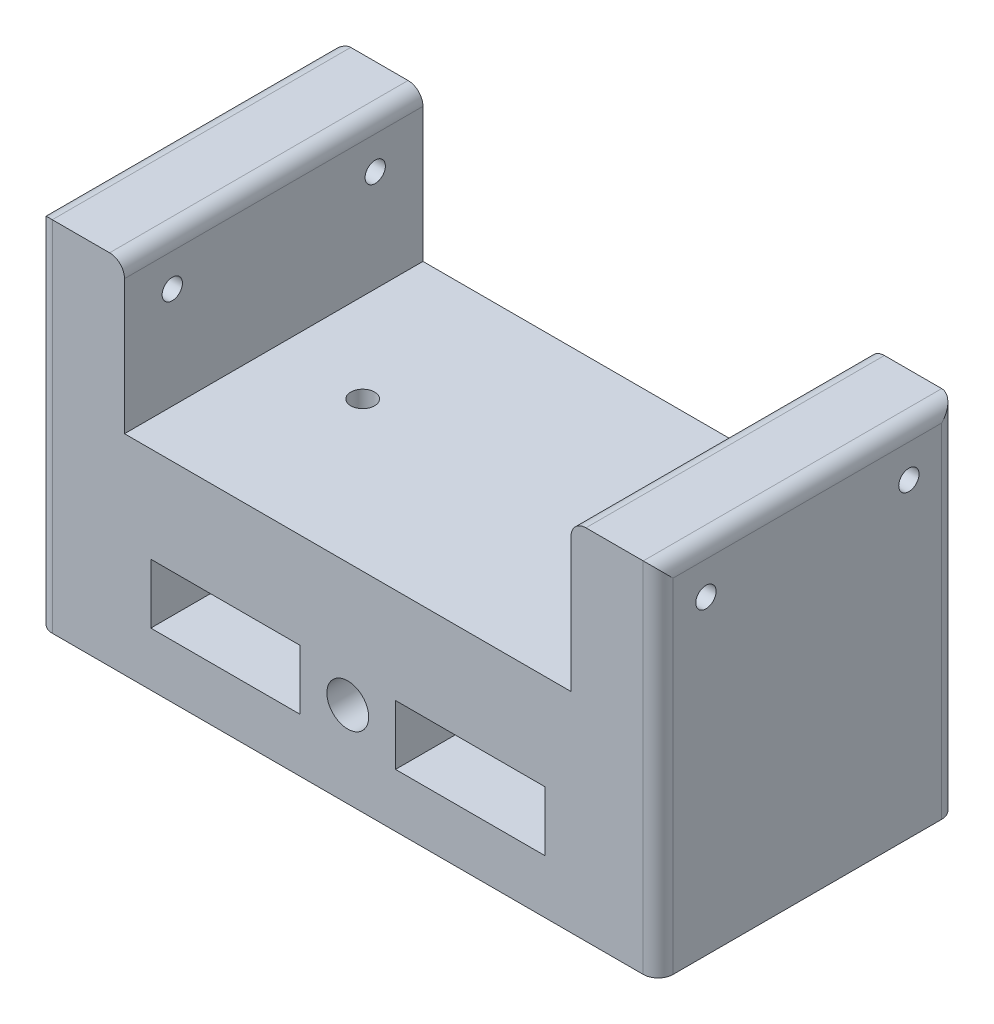
SolidWorks part; units mm, degrees
ref_plane "Front Plane" through (0, 0, 0) normal (0, 0, 1) x (1, 0, 0)
ref_plane "Top Plane" through (0, 0, 0) normal (0, 1, 0) x (1, 0, 0)
ref_plane "Right Plane" through (0, 0, 0) normal (1, 0, 0) x (0, 0, -1)
sketch "Sketch1" plane through (0, 0, 0) normal (0, 1, 0) x (1, 0, 0)
  line L0 (-63.2444, 0) -> (60.1177, 0) construction
  line L1 (-52, 25) -> (-52, -25)
  line L2 (-52, -25) -> (52, -25)
  line L3 (52, -25) -> (52, 25)
  line L4 (-52, 25) -> (52, 25)
  line L5 (0, -25) -> (0, 25) construction
  point P8 (52, 0)
  point P9 (-52, 0)
  dimension "D1" = 52
  dimension "D2" = 52
  dimension "D3" = 25
extrude "Boss-Extrude1" add sketch "Sketch1" along normal blind 10
sketch "Sketch2" plane through (0, 0, 0) normal (0, -1, 0) x (1, 0, 0)
  line L0 (0, 25) -> (0, -25) construction
  line L1 (-52, 25) -> (52, 25) construction
  line L2 (52, -25) -> (-52, -25) construction
  line L3 (-52, 0) -> (52, 0) construction
  line L4 (-52, -25) -> (-52, 25) construction
  line L5 (52, 25) -> (52, -25) construction
  line L6 (-45.5, 13.5) -> (-45.5, 0)
  line L7 (-45.5, 0) -> (-45.5, -13.5)
  line L8 (-45.5, -13.5) -> (0, -13.5)
  line L9 (0, -13.5) -> (45.5, -13.5)
  line L10 (45.5, -13.5) -> (45.5, 0)
  line L11 (45.5, 0) -> (45.5, 13.5)
  line L12 (45.5, 13.5) -> (0, 13.5)
  line L13 (0, 13.5) -> (-45.5, 13.5)
  line L14 (-52, 25) -> (52, 25)
  line L15 (52, 25) -> (52, -25)
  line L16 (52, -25) -> (-52, -25)
  line L17 (-52, -25) -> (-52, 25)
  dimension "D1" = 13.5
  dimension "D2" = 45.5
extrude "Boss-Extrude2" add sketch "Sketch2" along normal blind 25
sketch "Sketch3" plane through (0, 10, 0) normal (0, 1, 0) x (1, 0, 0)
  line L0 (0, 25) -> (0, -25) construction
  line L1 (52, 25) -> (-52, 25) construction
  line L2 (-52, -25) -> (52, -25) construction
  line L3 (-52, 25) -> (-37.4, 25)
  line L4 (-37.4, 25) -> (-37.4, -25)
  line L5 (-37.4, -25) -> (-52, -25)
  line L6 (-52, -25) -> (-52, 25)
  line L7 (37.4, 25) -> (52, 25)
  line L8 (52, 25) -> (52, -25)
  line L9 (52, -25) -> (37.4, -25)
  line L10 (37.4, -25) -> (37.4, 25)
  dimension "D1" = 74.8
extrude "Boss-Extrude3" add sketch "Sketch3" along normal blind 25
sketch "Sketch4" plane through (52, 0, 0) normal (1, 0, 0) x (0, 0, -1)
  line L0 (0, 35) -> (0, -25) construction
  line L1 (-25, 35) -> (25, 35) construction
  line L2 (25, -25) -> (-25, -25) construction
  line L3 (25, 35) -> (25, -25) construction
  circle A1 centre (17, 27) radius 1.7
  circle A2 centre (-17, 27) radius 1.7
  dimension "D1" = 8
  dimension "D2" = 3.4
  dimension "D3" = 8
extrude "Cut-Extrude1" cut sketch "Sketch4" against normal through all and the other way through all
sketch "Sketch5" plane through (0, 10, 0) normal (0, 1, 0) x (1, 0, 0)
  line L0 (-37.4, 0) -> (37.4, 0) construction
  line L1 (-37.4, -25) -> (-37.4, 25) construction
  line L2 (37.4, 25) -> (37.4, -25) construction
  line L3 (0, 25) -> (0, -25) construction
  line L4 (37.4, 25) -> (-37.4, 25) construction
  line L5 (-37.4, -25) -> (37.4, -25) construction
  circle A0 centre (-22.5, 0) radius 2
  circle A1 centre (22.5, 0) radius 2
  dimension "D1" = 4
  dimension "D2" = 4
  dimension "D3" = 45
extrude "Cut-Extrude2" cut sketch "Sketch5" against normal through all and the other way through all
sketch "Sketch8" plane through (0, 0, 25) normal (0, 0, 1) x (1, 0, 0)
  line L0 (0, 0) -> (0, -25) construction
  line L1 (52, -25) -> (-52, -25) construction
  line L3 (45.5, 0) -> (-45.5, 0) construction
  circle A0 centre (0, -10.65) radius 3.5
  dimension "D1" = 7
  dimension "D2" = 10.65
extrude "Cut-Extrude4" cut sketch "Sketch8" against normal up to next and the other way through all
fillet "Fillet1" radius 2.5 8 edges at (-52, 5, -25) (52, 5, -25) (52, 5, 25) (-52, 5, 25) (-52, 35, 0) (52, 35, 0) (37.4, 35, 0) (-37.4, 35, 0)
sketch "Sketch9" plane through (0, 0, -25) normal (0, 0, -1) x (-1, 0, 0)
  line L0 (0, 10) -> (0, -25) construction
  line L1 (-37.4, 10) -> (37.4, 10) construction
  line L2 (49.5, -25) -> (-49.5, -25) construction
  line L5 (-33, -6) -> (-33, -16)
  line L8 (-33, -6) -> (0, -6)
  line L11 (33, -6) -> (33, -16)
  line L13 (0, -6) -> (33, -6)
  line L14 (-33, -16) -> (0, -16)
  line L15 (0, -16) -> (33, -16)
  dimension "D1" = 33
  dimension "D2" = 9
  dimension "D4" = 10
extrude "Cut-Extrude6" cut sketch "Sketch9" against normal up to next and the other way through all
sketch "Sketch10" plane through (0, 0, 25) normal (0, 0, 1) x (1, 0, 0)
  line L0 (0, 0) -> (0, -25) construction
  line L1 (45.5, 0) -> (-45.5, 0) construction
  line L2 (49.5, -25) -> (-49.5, -25) construction
  line L3 (-33, -6) -> (-33, -16)
  line L4 (-33, -16) -> (-8, -16)
  line L5 (33, -16) -> (-33, -16) construction
  line L6 (-8, -16) -> (-8, -6)
  line L7 (-33, -6) -> (33, -6) construction
  line L8 (-8, -6) -> (-33, -6)
  line L9 (8, -6) -> (33, -6)
  line L10 (8, -16) -> (8, -6)
  line L11 (33, -16) -> (8, -16)
  line L12 (33, -6) -> (33, -16)
  dimension "D1" = 8
extrude "Cut-Extrude7" cut sketch "Sketch10" against normal up to next and the other way through all
